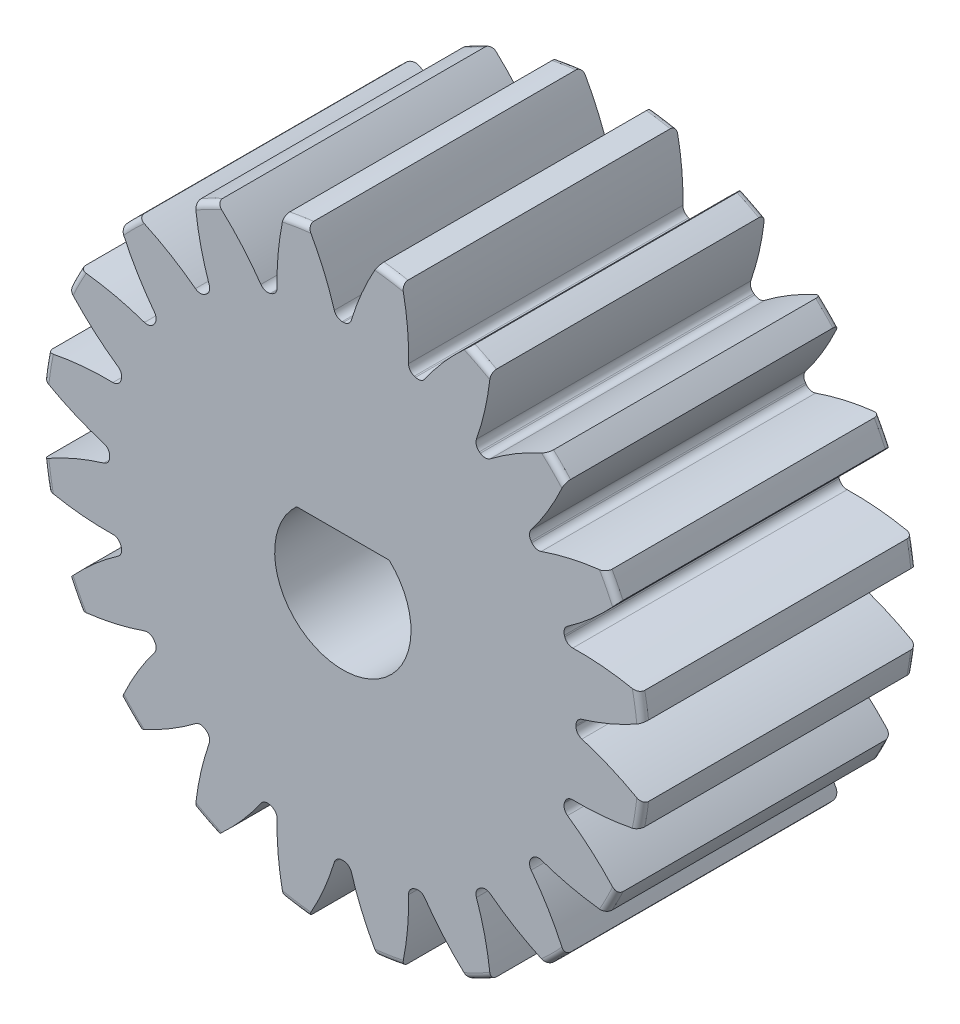
SolidWorks part; units mm, degrees
ref_plane "Front Plane" through (0, 0, 0) normal (0, 0, 1) x (1, 0, 0)
ref_plane "Top Plane" through (0, 0, 0) normal (0, 1, 0) x (1, 0, 0)
ref_plane "Right Plane" through (0, 0, 0) normal (1, 0, 0) x (0, 0, -1)
sketch "Sketch1" plane through (0, 0, 0) normal (0, 0, 1) x (1, 0, 0)
  line L0 (-254, 0) -> (254, 0) construction
  circle A0 centre (0, 0) radius 13.97 construction
  circle A1 centre (0, 0) radius 12.7 construction
  circle A2 centre (0, 0) radius 10.795 construction
  circle A3 centre (0, 0) radius 10.8331 construction
  circle A4 centre (0, 0) radius 6.35 construction
  circle A5 centre (0, 0) radius 10.3187 construction
  dimension "D2" = 1.27
  dimension "D3" = 3.175
  dimension "D1" = 3.175
sketch "Sketch2" plane through (0, 0, 0) normal (1, 0, 0) x (0, 0, -1)
  line L0 (0, 0) -> (-12.7, 0) construction
  line L1 (-12.7, 0) -> (-23.8252, 0) construction
  dimension "Overall Width" = 23.8252
  dimension "Face Width" = 12.7
sketch "Sketch4" plane through (0, 0, 0) normal (1, 0, 0) x (0, 0, -1)
  line L0 (-23.8252, 6.35) -> (-23.8252, 10.8331)
  line L1 (-23.8252, 10.8331) -> (-12.7, 10.8331)
  line L2 (-12.7, 10.8331) -> (-12.7, 13.97)
  line L3 (-12.7, 13.97) -> (0, 13.97)
  line L4 (0, 13.97) -> (0, 6.35)
  line L5 (-12.7, 10.8331) -> (-12.7, 0) construction
  line L6 (0, 13.97) -> (0, -13.97) construction
  line L7 (-12.7, 10.8331) -> (0, 10.8331) construction
  line L12 (-23.8252, 6.35) -> (0, 6.35)
revolve "Revolve1" add sketch "Sketch4" angle 360 about L1
fillet "Fillet2" radius 0.2794 4 edges at (0, 10.8331, 23.8252) (0, 10.8331, 12.7) (0, 13.97, 12.7) (0, 13.97, 0)
sketch "Sketch7" plane through (0, 0, 12.7) normal (0, 0, 1) x (1, 0, 0)
  line L0 (0, 0) -> (0, 13.97) construction
  line L1 (0.9964, 12.6609) -> (1.5536, 13.8833) construction
  line L3 (2.1854, 13.798) -> (1.9867, 12.5436) construction
  line L4 (1.9867, 12.5436) -> (1.6887, 10.6621) construction
  line L5 (0, 0) -> (1.6887, 10.6621) construction
  line L6 (0.9964, 12.6609) -> (0, 0) construction
  line L7 (0.9964, 12.6609) -> (1.0961, 13.9269) construction
  line L8 (0.9964, 12.6609) -> (0, 0) construction
  circle A0 centre (0, 0) radius 13.97 construction
  arc A1 (-0.0294, 10.795) -> (0.0294, 10.795) centre (0, 0) cw
  circle A2 centre (0, 0) radius 10.795 construction
  arc A3 (-0.9964, 12.6609) -> (0.9964, 12.6609) centre (0, 0) cw construction
  circle A4 centre (0, 0) radius 12.7 construction
  arc A5 (2.7366, 13.6993) -> (1.6307, 13.8745) centre (0, 0) ccw construction
  arc A6 (0.9964, 12.6609) -> (2.9648, 12.3491) centre (0, 0) cw construction
  arc A7 (-1.6307, 13.8745) -> (1.6307, 13.8745) centre (0, 0) cw
  arc A8 (0.3952, 11.0658) -> (1.6307, 13.8745) centre (12.5529, 7.3942) cw
  arc A9 (-0.3952, 11.0658) -> (-1.6307, 13.8745) centre (-12.5529, 7.3942) ccw
  arc A10 (-0.0294, 10.795) -> (-0.3952, 11.0658) centre (-0.0305, 11.176) cw
  arc A11 (0.0294, 10.795) -> (0.3952, 11.0658) centre (0.0305, 11.176) ccw
  point P26 (-0.3154, 10.7904)
  point P29 (0.3154, 10.7904)
  dimension "D4" = 0.381
  dimension "D5" = 12.7
  dimension "D3" = 20
  dimension "D1" = 3.9898
  dimension "D2" = 1.9949
extrude "Cut-Extrude2" cut sketch "Sketch7" against normal through all
pattern_circular "CirPattern1" count 20 over 360 about axis through (0, 0, 0) along (0, 0, 1) of "Cut-Extrude2"
sketch "Sketch9" [suppressed] plane through (0, 0, 0) normal (0, 0, 1) x (1, 0, 0)
  circle A0 centre (0, 0) radius 10.3187 construction
  circle A1 centre (0, 0) radius 10.3187
sketch "Sketch11" plane through (0, 0, 23.8252) normal (0, 0, 1) x (1, 0, 0)
  circle A0 centre (0, 0) radius 11.43
  dimension "D1" = 22.86
extrude "Cut-Extrude3" cut sketch "Sketch11" against normal blind 11.1252
sketch "Sketch13" plane through (0, 0, 12.7) normal (0, 0, 1) x (1, 0, 0)
  circle A0 centre (0, 0) radius 6.35
  dimension "D1" = 12.7
extrude "Boss-Extrude1" add sketch "Sketch13" against normal blind 12.7
sketch "Sketch15" plane through (0, 0, 0) normal (0, 0, -1) x (-1, 0, 0)
  circle A0 centre (0, 0) radius 6.35
  dimension "D1" = 12.7
extrude "Cut-Extrude4" cut sketch "Sketch15" against normal blind 6.35
sketch "Sketch16" plane through (0, 0, 12.7) normal (0, 0, 1) x (1, 0, 0)
  line L0 (0, -3.1559) -> (0, 2.3178) construction
  line L1 (-2.142, 2.3178) -> (2.142, 2.3178)
  circle A0 centre (0, 0) radius 3.156
  dimension "D1" = 6.3119
  dimension "D2" = 5.4737
extrude "Cut-Extrude5" cut sketch "Sketch16" against normal through all contours A0 L0 L1 | L0 A0 L1
equation "\"D1@Sketch1\"=2.5*(\"Pitch Dia.@Sketch1\"/\"Number of Teeth@Sketch1\")"
equation "\"D1@CirPattern1\"=\"Number of Teeth@Sketch1\""
equation "\"D1@Fillet2\"=\"OD@Sketch1\"*.01"
equation "\"D1@Sketch7\"=3.14159*(\"Pitch Dia.@Sketch1\"/\"Number of Teeth@Sketch1\")"
equation "\"D2@Sketch7\"=\"D1@Sketch7\"/2"
equation "\"D4@Sketch7\"=\"D1@Sketch7\"*.0955"
equation "\"D5@Sketch7\"=\"Pitch Dia.@Sketch1\"/2"
